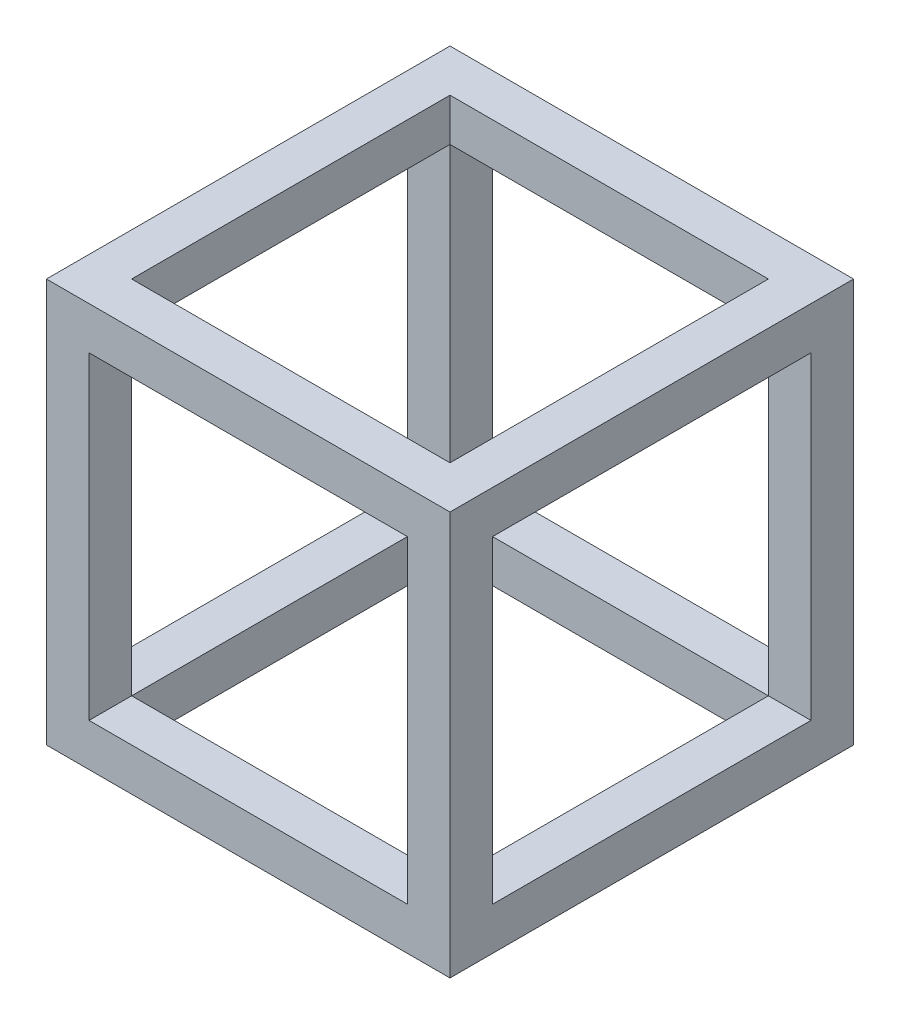
SolidWorks part; units mm, degrees
material "6061 Alloy"
ref_plane "Front Plane" through (0, 0, 0) normal (0, 0, 1) x (1, 0, 0)
ref_plane "Top Plane" through (0, 0, 0) normal (0, 1, 0) x (1, 0, 0)
ref_plane "Right Plane" through (0, 0, 0) normal (1, 0, 0) x (0, 0, -1)
sketch "Sketch1" plane through (0, 0, 0) normal (0, 1, 0) x (1, 0, 0)
  line L1 (0, 0) -> (228.6, 0)
  line L2 (0, 0) -> (0, -228.6)
  line L3 (0, -228.6) -> (228.6, -228.6)
  line L4 (228.6, 0) -> (228.6, -228.6)
  dimension "D1" = 228.6
extrude "Boss-Extrude1" add sketch "Sketch1" along normal blind 228.6
sketch "Sketch2" plane through (0, 0, 0) normal (0, 0, 1) x (1, 0, 0)
  line L0 (0, 228.6) -> (228.6, 228.6) construction
  line L1 (24.13, 204.47) -> (204.47, 204.47)
  line L2 (24.13, 204.47) -> (24.13, 24.13)
  line L3 (24.13, 24.13) -> (204.47, 24.13)
  line L4 (204.47, 204.47) -> (204.47, 24.13)
  line L5 (228.6, 228.6) -> (228.6, 0) construction
  point P4 (18.7372, 204.6725)
  point P7 (114.3, 228.6)
  point P8 (114.3, 204.47)
  point P11 (228.6, 114.3)
  point P12 (204.47, 114.3)
  dimension "D1" = 180.34
extrude "Cut-Extrude2" cut sketch "Sketch2" along direction (0, 0, -1) on the side against the normal through all and the other way through all
sketch "Sketch3" plane through (0, 0, 0) normal (1, 0, 0) x (0, 0, -1)
  line L0 (0, 228.6) -> (0, 0) construction
  line L1 (-204.47, 204.47) -> (-24.13, 204.47)
  line L2 (-204.47, 204.47) -> (-204.47, 24.13)
  line L3 (-204.47, 24.13) -> (-24.13, 24.13)
  line L4 (-24.13, 204.47) -> (-24.13, 24.13)
  line L5 (-228.6, 228.6) -> (0, 228.6) construction
  point P6 (0, 114.3)
  point P7 (-24.13, 114.3)
  point P10 (-114.3, 228.6)
  point P11 (-114.3, 204.47)
  dimension "D1" = 180.34
extrude "Cut-Extrude4" cut sketch "Sketch3" along normal through all
sketch "Sketch4" plane through (0, 0, 0) normal (0, 1, 0) x (1, 0, 0)
  line L0 (228.6, 0) -> (0, 0) construction
  line L1 (24.13, -24.13) -> (204.47, -24.13)
  line L2 (24.13, -24.13) -> (24.13, -204.47)
  line L3 (24.13, -204.47) -> (204.47, -204.47)
  line L4 (204.47, -24.13) -> (204.47, -204.47)
  line L5 (228.6, -228.6) -> (228.6, 0) construction
  point P6 (114.3, 0)
  point P7 (114.3, -24.13)
  point P10 (228.6, -114.3)
  point P11 (204.47, -114.3)
  dimension "D1" = 180.34
extrude "Cut-Extrude5" cut sketch "Sketch4" along normal through all
